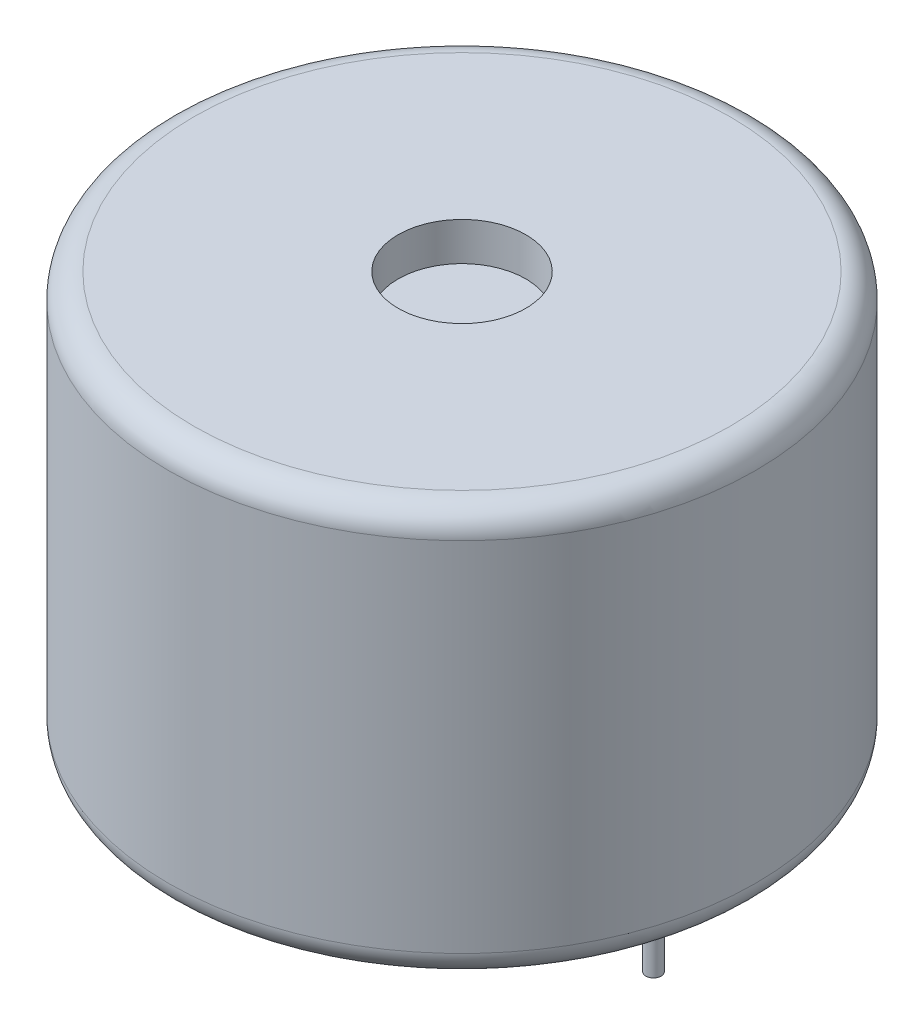
SolidWorks part; units mm, degrees
ref_plane "前视基准面" through (0, 0, 0) normal (0, 0, 1) x (1, 0, 0)
ref_plane "上视基准面" through (0, 0, 0) normal (0, 1, 0) x (1, 0, 0)
ref_plane "右视基准面" through (0, 0, 0) normal (1, 0, 0) x (0, 0, -1)
sketch "草图1" plane through (0, 0, 0) normal (0, 1, 0) x (1, 0, 0)
  circle A0 centre (0, 0) radius 11.5
  dimension "D1" = 23
extrude "凸台-拉伸1" add sketch "草图1" along normal blind 16
sketch "草图2" plane through (0, 0, 0) normal (0, -1, 0) x (1, 0, 0)
  line L0 (0, 8.6766) -> (0, -8.6766) construction
  circle A0 centre (-7.5, 0) radius 0.3
  circle A1 centre (7.5, 0) radius 0.3
  point P8 (0, 0)
  dimension "D2" = 0.6
  dimension "D1" = 15
extrude "凸台-拉伸2" add sketch "草图2" along normal blind 4
sketch "草图3" plane through (0, 19, 0) normal (0, 0, -1) x (1, 0, 0)
  line L0 (0, -15.2402) -> (0, 21.2402) construction
  line L2 (0, 3) -> (-2.5, 3)
  line L3 (-11.5, 3) -> (11.5, 3) construction
  line L4 (-2.5, 3) -> (-2.5, 4.5)
  line L5 (-2.5, 4.5) -> (-10, 4.5)
  line L6 (-10, 4.5) -> (-10, 8)
  line L7 (-10, 8) -> (0, 8)
  line L8 (0, 8) -> (0, 3)
  line L9 (-11.5, 19) -> (-11.5, 3) construction
  point P7 (0, 3)
  dimension "D1" = 5
  dimension "D2" = 1.5
  dimension "D3" = 1.5
  dimension "D4" = 5
revolve "切除-旋转1" cut sketch "草图3" angle 360 about L0
fillet "圆角1" radius 1 2 edges at (0, 16, 11.5) (0, 0, 11.5)
